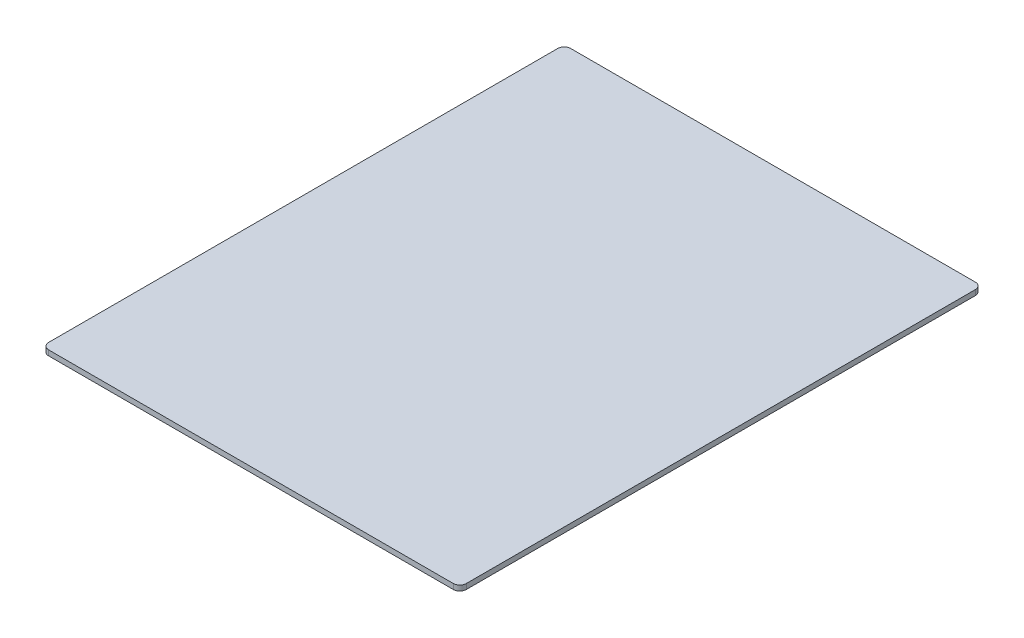
SolidWorks part; units mm, degrees
ref_plane "Front Plane" through (0, 0, 0) normal (0, 0, 1) x (1, 0, 0)
ref_plane "Top Plane" through (0, 0, 0) normal (0, 1, 0) x (1, 0, 0)
ref_plane "Right Plane" through (0, 0, 0) normal (1, 0, 0) x (0, 0, -1)
sketch "Sketch1" plane through (0, 0, 0) normal (0, 1, 0) x (1, 0, 0)
  line L1 (80, -100) -> (-80, -100)
  line L2 (80, -100) -> (80, 100)
  line L3 (80, 100) -> (-80, 100)
  line L4 (-80, -100) -> (-80, 100)
  line L5 (80, -100) -> (-80, 100) construction
  line L6 (80, 100) -> (-80, -100) construction
  point P0 (0, 0)
  dimension "D1" = 160
  dimension "D2" = 200
extrude "Boss-Extrude1" add sketch "Sketch1" along normal blind 2
fillet "Fillet1" radius 2.5 4 edges at (-80, 1, -100) (80, 1, -100) (80, 1, 100) (-80, 1, 100)
